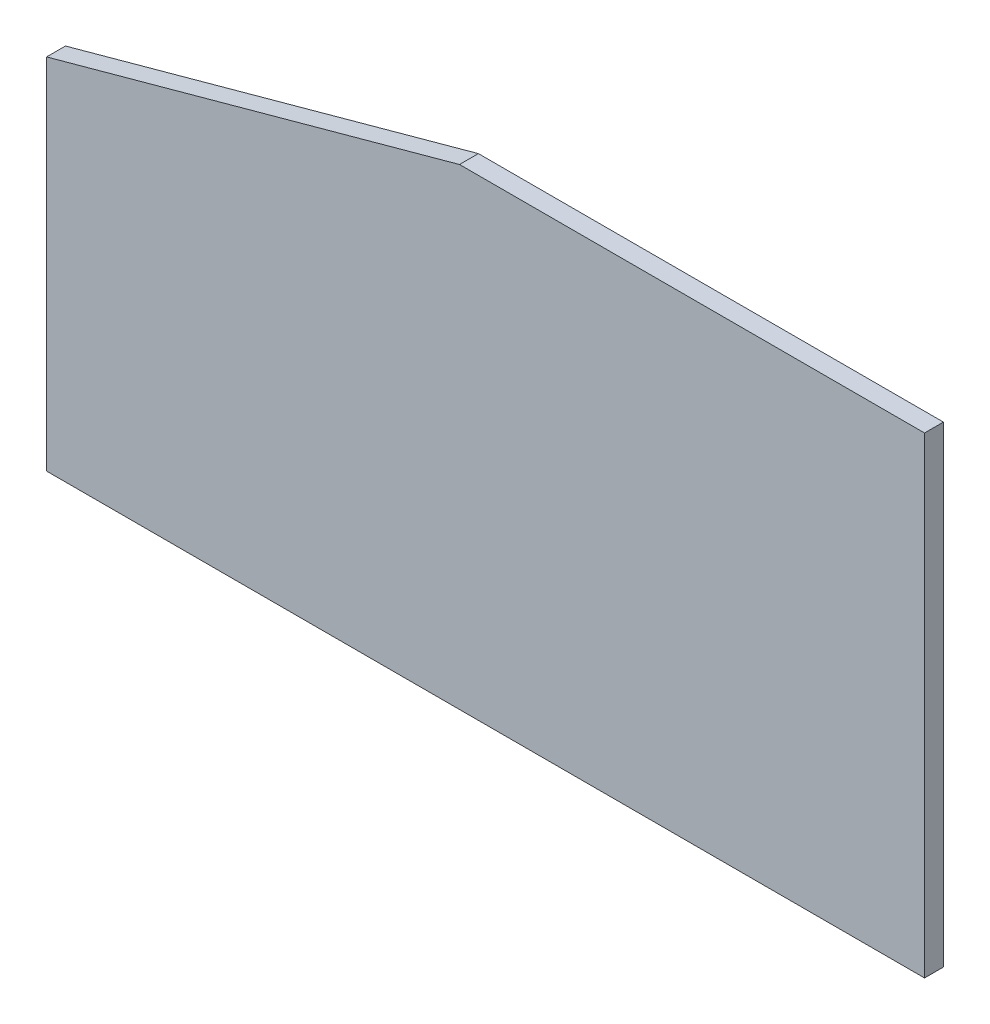
SolidWorks part; units mm, degrees
material "ASTM A36 Steel"
ref_plane "Front Plane" through (0, 0, 0) normal (0, 0, 1) x (1, 0, 0)
ref_plane "Top Plane" through (0, 0, 0) normal (0, 1, 0) x (1, 0, 0)
ref_plane "Right Plane" through (0, 0, 0) normal (1, 0, 0) x (0, 0, -1)
sketch "Sketch1" plane through (0, 0, 0) normal (0, 0, 1) x (1, 0, 0)
  line L0 (-389.5238, -57.2917) -> (-157.0238, -57.2917)
  line L1 (-157.0238, -57.2917) -> (-157.0238, 67.7083)
  line L2 (-157.0238, 67.7083) -> (-280.1766, 67.7083)
  line L3 (-389.5238, -57.2917) -> (-389.5238, 37.7083)
  line L5 (-389.5238, 37.7083) -> (-280.1766, 67.7083)
  dimension "D1" = 125
  dimension "D2" = 95
  dimension "D3" = 232.5
extrude "Boss-Extrude1" add sketch "Sketch1" along normal blind 5
